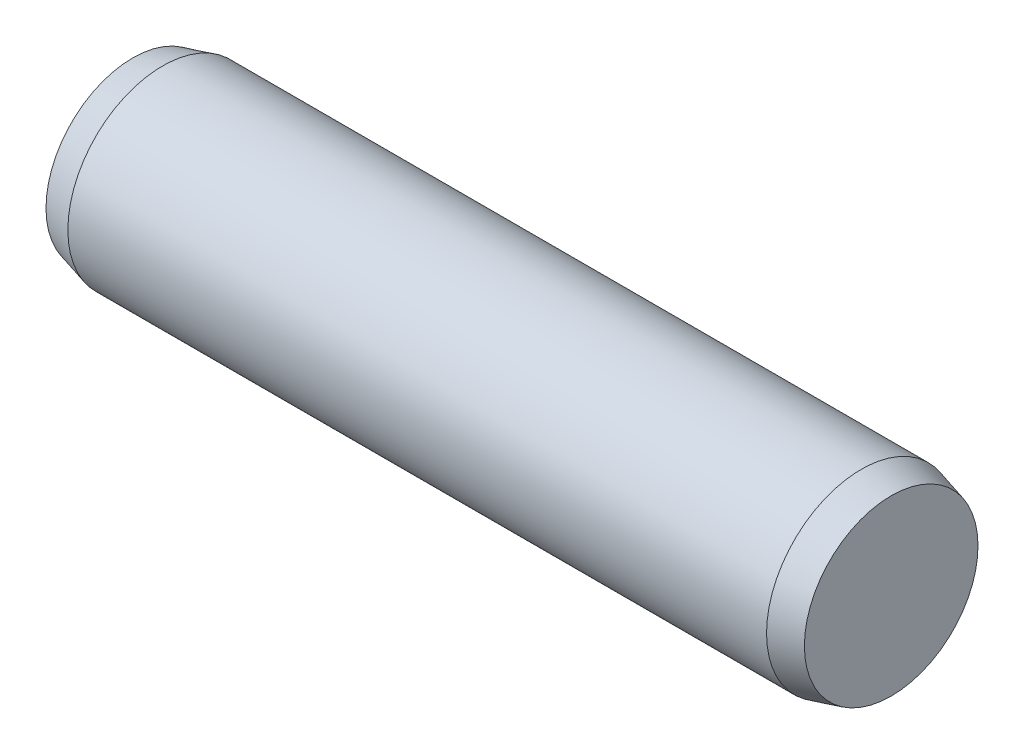
SolidWorks part; units mm, degrees
ref_plane "Plane1" through (0, 0, 0) normal (0, 0, 1) x (1, 0, 0)
ref_plane "Plane2" through (0, 0, 0) normal (0, 1, 0) x (1, 0, 0)
ref_plane "Plane3" through (0, 0, 0) normal (1, 0, 0) x (0, 0, -1)
sketch "Sketch1" plane through (0, 0, 0) normal (0, 0, 1) x (1, 0, 0)
  line L1 (-6.35, 0) -> (107.95, 0) construction
  line L2 (0, 0) -> (16, 0)
  line L3 (16, 0) -> (16, 1.8312)
  line L4 (16, 1.8312) -> (15.37, 2)
  line L5 (15.37, 2) -> (0.63, 2)
  line L6 (0, 1.8312) -> (0, 0)
  line L7 (0, 1.8312) -> (0.63, 2)
  dimension "D1" = 0.63
  dimension "D2" = 15
  dimension "D3" = 15
  dimension "Diameter" = 4
  dimension "Length" = 16
  dimension "Chamfer_len" = 0.63
revolve "Base-Revolve" add sketch "Sketch1" angle 360 about L1
equation "\"D3@Sketch1\" = 15.0"
equation "\"D1@Sketch1\" = \"Chamfer_len@Sketch1\""
equation "\"D2@Sketch1\" = \"D3@Sketch1\""
